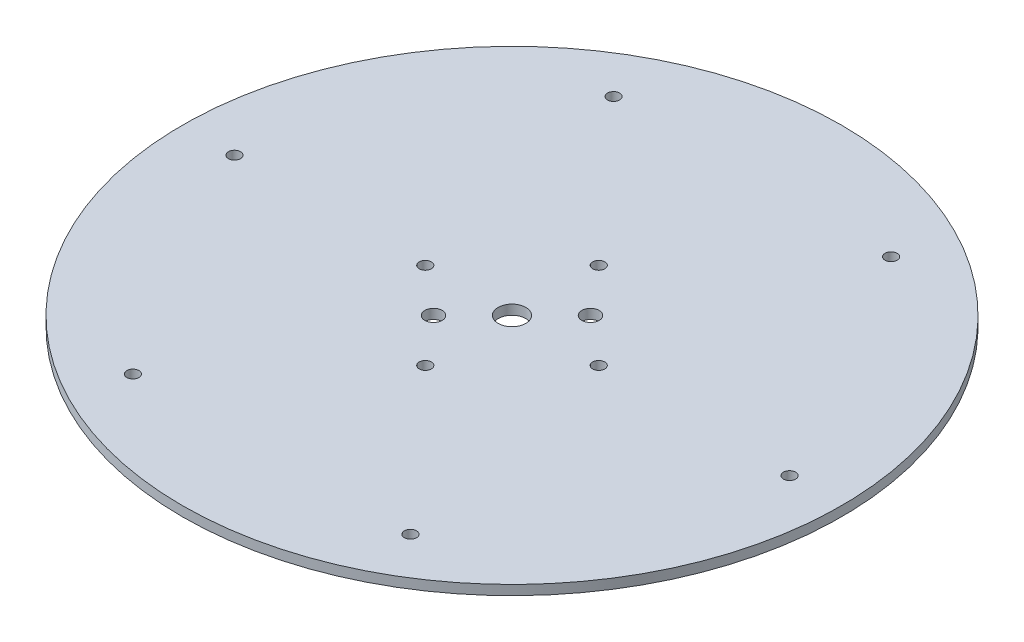
SolidWorks part; units mm, degrees
ref_plane "Front Plane" through (0, 0, 0) normal (0, 0, 1) x (1, 0, 0)
ref_plane "Top Plane" through (0, 0, 0) normal (0, 1, 0) x (1, 0, 0)
ref_plane "Right Plane" through (0, 0, 0) normal (1, 0, 0) x (0, 0, -1)
sketch "Sketch1" plane through (0, 0, 0) normal (0, 1, 0) x (1, 0, 0)
  line L0 (0, 0) -> (80, 0) construction
  line L1 (0, 0) -> (0, 25) construction
  circle A0 centre (0, 0) radius 95
  circle A1 centre (80, 0) radius 1.75
  circle A2 centre (40, -69.282) radius 1.75
  circle A3 centre (-40, -69.282) radius 1.75
  circle A4 centre (-80, 0) radius 1.75
  circle A5 centre (-40, 69.282) radius 1.75
  circle A6 centre (40, 69.282) radius 1.75
  circle A7 centre (0, 25) radius 1.75
  circle A8 centre (25, 0) radius 1.75
  circle A9 centre (0, -25) radius 1.75
  circle A10 centre (-25, 0) radius 1.75
  point P18 (0, 0)
  point P27 (0, 0)
  dimension "D1" = 190
  dimension "D3" = 3.5
  dimension "D6" = 3.5
  dimension "D2" = 80
  dimension "D5" = 25
  dimension "D4" = 6
  dimension "D7" = 4
extrude "Boss-Extrude1" add sketch "Sketch1" along normal blind 2.8
sketch "Sketch2" plane through (0, 2.8, 0) normal (0, 1, 0) x (1, 0, 0)
  line L0 (0, 0) -> (11.3137, 11.3137) construction
  circle A0 centre (0, 0) radius 4
  circle A1 centre (11.3137, 11.3137) radius 2.5
  circle A2 centre (-11.3137, -11.3137) radius 2.5
  point P10 (0, 0)
  dimension "D1" = 8
  dimension "D3" = 5
  dimension "D2" = 16
  dimension "D4" = 2
extrude "Cut-Extrude1" cut sketch "Sketch2" against normal blind 10
